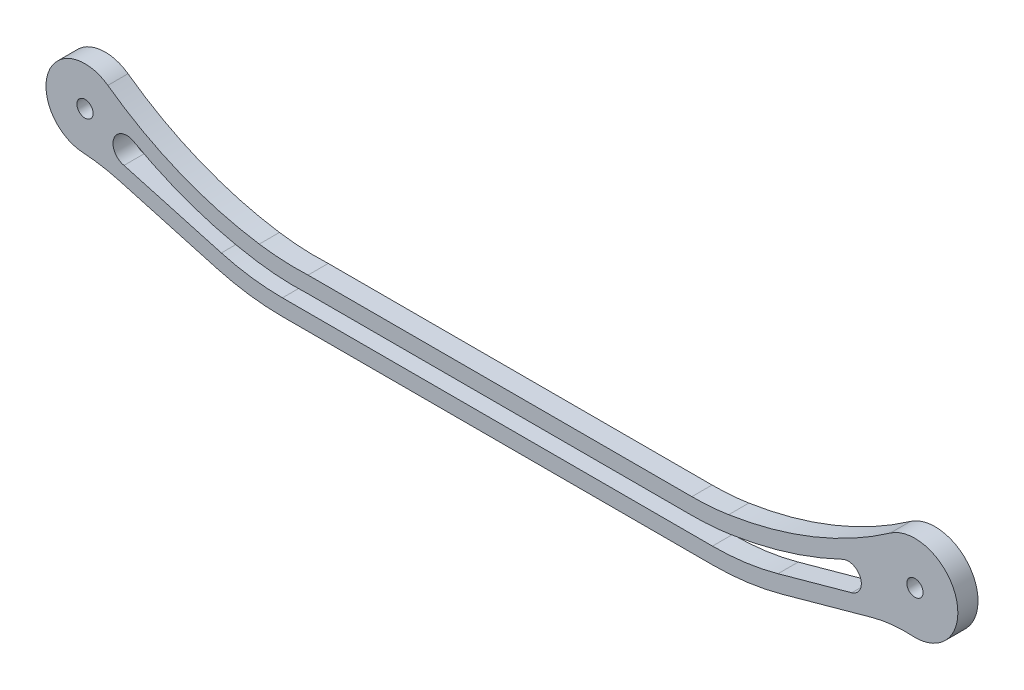
SolidWorks part; units mm, degrees
ref_plane "Front Plane" through (0, 0, 0) normal (0, 0, 1) x (1, 0, 0)
ref_plane "Top Plane" through (0, 0, 0) normal (0, 1, 0) x (1, 0, 0)
ref_plane "Right Plane" through (0, 0, 0) normal (1, 0, 0) x (0, 0, -1)
sketch "Sketch1" plane through (0, 0, 0) normal (0, 0, 1) x (1, 0, 0)
  line L2 (-116.9384, -13.9116) -> (-87, -22.25)
  line L3 (-66.8769, -25) -> (65.3265, -25)
  line L4 (86.8192, -22.0867) -> (114.2909, -14.5)
  line L11 (59, -10) -> (-59, -10)
  line L18 (-127.575, 0) -> (127.575, 0) construction
  line L19 (-115.5968, -9.0949) -> (-85.6585, -17.4333)
  line L20 (85.4882, -17.2672) -> (108.1527, -11.008)
  line L21 (59, -15) -> (-59, -15)
  line L22 (-66.8769, -20) -> (65.3265, -20)
  line L23 (85.4882, -17.2672) -> (112.9599, -9.6804) construction
  circle A0 centre (127.575, 0) radius 2.5
  circle A1 centre (-127.575, 0) radius 2.5
  arc A3 (-120.5545, 9.7321) -> (-128.3494, -11.975) centre (-127.575, 0) ccw
  arc A4 (-116.9384, -13.9116) -> (-128.3494, -11.975) centre (-131.9636, -67.8582) ccw
  arc A5 (-87, -22.25) -> (-66.8769, -25) centre (-66.8769, 50) ccw
  arc A6 (65.3265, -25) -> (86.8192, -22.0867) centre (65.3265, 55.7384) ccw
  arc A8 (126.8, -13.1772) -> (120, 10.8102) centre (127.575, 0) ccw
  arc A10 (59, -10) -> (70.3289, -9.1348) centre (59, 64.6) ccw
  arc A11 (-74, -9.25) -> (-59, -10) centre (-62.741, 65.5556) ccw
  arc A22 (-120.5545, 9.7321) -> (-74, -9.25) centre (-58.1155, 96.2872) ccw
  arc A25 (114.2909, -14.5) -> (126.8, -13.1772) centre (124.5396, -51.6108) cw
  arc A26 (70.3289, -9.1348) -> (120, 10.8102) centre (52.4542, 107.2039) ccw
  arc A27 (-112.6476, -1.2265) -> (-74.7442, -14.1943) centre (-58.1155, 96.2872) ccw
  arc A28 (-74.7442, -14.1943) -> (-58.8783, -15) centre (-62.741, 65.5556) ccw
  arc A29 (-85.6585, -17.4333) -> (-66.8769, -20) centre (-66.8769, 50) ccw
  arc A30 (-123.4797, 5.677) -> (-74.7442, -14.1943) centre (-58.1155, 96.2872) ccw construction
  arc A31 (-74.7442, -14.1943) -> (-58.7527, -14.9939) centre (-62.741, 65.5556) ccw construction
  arc A32 (-115.5968, -9.0949) -> (-112.6476, -1.2265) centre (-114.722, -4.9359) cw
  arc A33 (65.3265, -20) -> (85.4882, -17.2672) centre (65.3265, 55.7384) ccw
  arc A34 (59, -15) -> (71.0882, -14.0768) centre (59, 64.6) ccw
  arc A35 (71.0882, -14.0768) -> (105.3519, -3.5122) centre (52.4542, 107.2039) ccw
  arc A36 (105.3519, -3.5122) -> (108.1527, -11.008) centre (107.0834, -7.1364) cw
  arc A38 (71.0882, -14.0768) -> (122.8693, 6.7154) centre (52.4542, 107.2039) ccw construction
  dimension "D1" = 127.575
  dimension "D2" = 5
  dimension "D5" = 12
  dimension "D7" = 59
  dimension "D9" = 9.25
  dimension "D10" = 75.6482
  dimension "D12" = 75
  dimension "D14" = 56
  dimension "D15" = 74.6
  dimension "D17" = 126.8
  dimension "D18" = 13.2
  dimension "D23" = 5
  dimension "D25" = 4.25
  dimension "D28" = 4.0166
  dimension "D3" = 10
  dimension "D4" = 15
  dimension "D6" = 59
  dimension "D8" = 74
  dimension "D11" = 22.25
  dimension "D13" = 87
  dimension "D16" = 120
  dimension "D19" = 28.5
  dimension "D20" = 14.5
  dimension "D21" = 5
  dimension "D22" = 5
  dimension "D24" = 5
  dimension "D26" = 5
  dimension "D27" = 5
extrude "Boss-Extrude1" add sketch "Sketch1" along normal blind 6.2
